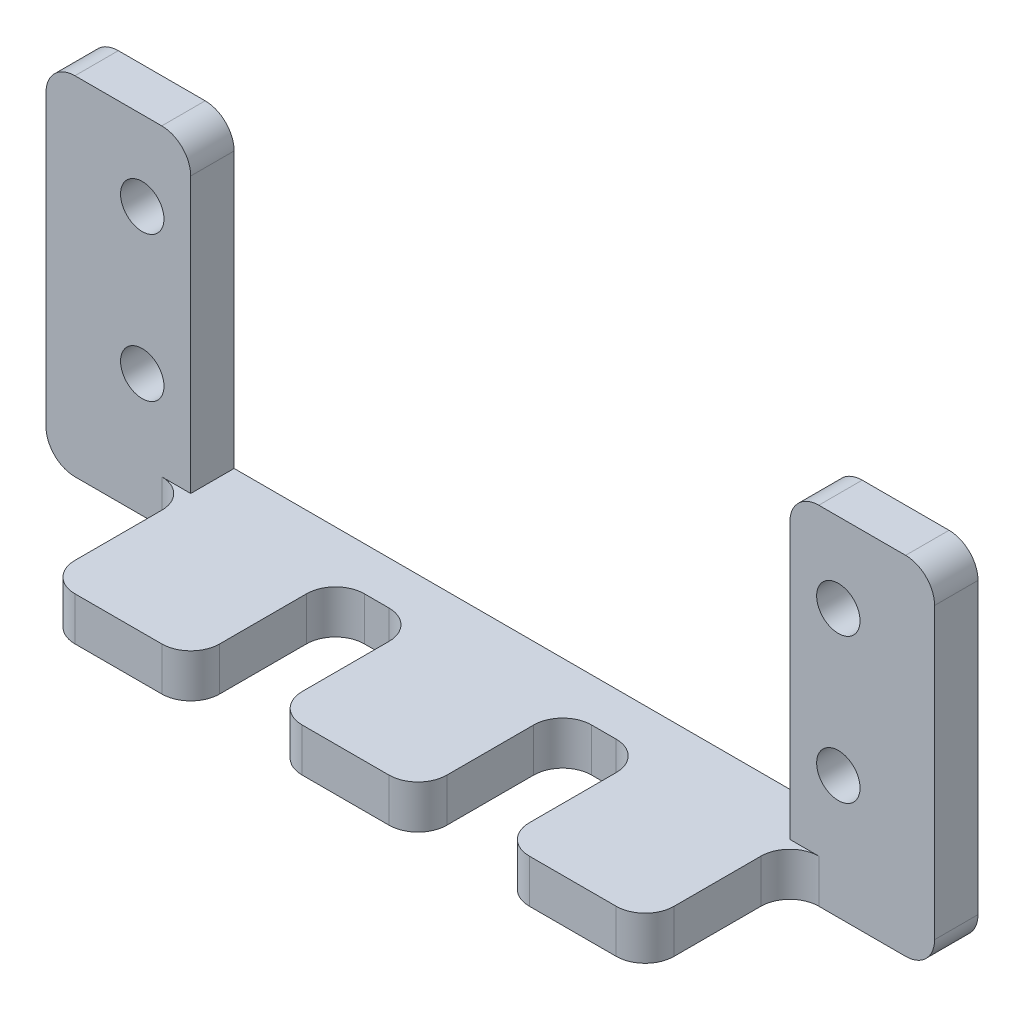
SolidWorks part; units mm, degrees
ref_plane "Front Plane" through (0, 0, 0) normal (0, 0, 1) x (1, 0, 0)
ref_plane "Top Plane" through (0, 0, 0) normal (0, 1, 0) x (1, 0, 0)
ref_plane "Right Plane" through (0, 0, 0) normal (1, 0, 0) x (0, 0, -1)
sketch "Sketch1" plane through (0, 0, 0) normal (0, 0, 1) x (1, 0, 0)
  line L0 (10, 24) -> (10, 3)
  line L1 (0, 0) -> (61.4, 0)
  line L2 (0, 0) -> (0, 24)
  line L3 (0, 24) -> (10, 24)
  line L4 (61.4, 0) -> (61.4, 24)
  line L5 (10, 3) -> (51.4, 3)
  line L6 (51.4, 3) -> (51.4, 24)
  line L7 (51.4, 24) -> (61.4, 24)
  line L8 (10, 13.5) -> (35.3794, 13.5) construction
  circle A0 centre (6.65, 8.5) radius 1.5
  circle A1 centre (6.65, 18.5) radius 1.5
  circle A2 centre (54.75, 18.5) radius 1.5
  circle A3 centre (54.75, 8.5) radius 1.5
  dimension "D4" = 3
  dimension "D5" = 10
  dimension "D8" = 3.35
  dimension "D9" = 3.35
  dimension "D10" = 10
  dimension "D11" = 5
  dimension "D12" = 5
  dimension "D13" = 3.35
  dimension "D14" = 3.35
  dimension "D1" = 41.4
  dimension "D2" = 21
  dimension "D3" = 3
  dimension "D6" = 10
  dimension "D7" = 10
extrude "Boss-Extrude1" add sketch "Sketch1" along normal blind 3
sketch "Sketch2" plane through (0, 0, 3) normal (0, 0, 1) x (1, 0, 0)
  line L0 (0, 0) -> (61.4, 0) construction
  line L1 (10, 3) -> (20, 3)
  line L2 (10, 3) -> (10, 0)
  line L3 (10, 0) -> (20, 0)
  line L4 (51.4, 3) -> (51.4, 0)
  line L5 (20, 3) -> (20, 0)
  line L6 (41.4, 3) -> (41.4, 0)
  line L7 (35.7, 3) -> (35.7, 0)
  line L8 (25.7, 0) -> (25.7, 3)
  line L9 (25.7, 3) -> (35.7, 3)
  line L10 (25.7, 0) -> (35.7, 0)
  line L11 (41.4, 3) -> (51.4, 3)
  line L12 (41.4, 0) -> (51.4, 0)
  dimension "D1" = 41.4
  dimension "D2" = 10
  dimension "D3" = 10
  dimension "D4" = 10
  dimension "D5" = 5.7
extrude "Boss-Extrude2" add sketch "Sketch2" along normal blind 10
fillet "Fillet1" radius 2 18 edges at (10, 1.5, 3) (51.4, 1.5, 3) (20, 1.5, 3) (10, 1.5, 13) (20, 1.5, 13) (25.7, 1.5, 3) (41.4, 1.5, 3) (35.7, 1.5, 3) (25.7, 1.5, 13) (35.7, 1.5, 13) (41.4, 1.5, 13) (51.4, 1.5, 13) (51.4, 24, 1.5) (61.4, 24, 1.5) (61.4, 0, 1.5) (0, 0, 1.5) (0, 24, 1.5) (10, 24, 1.5)
